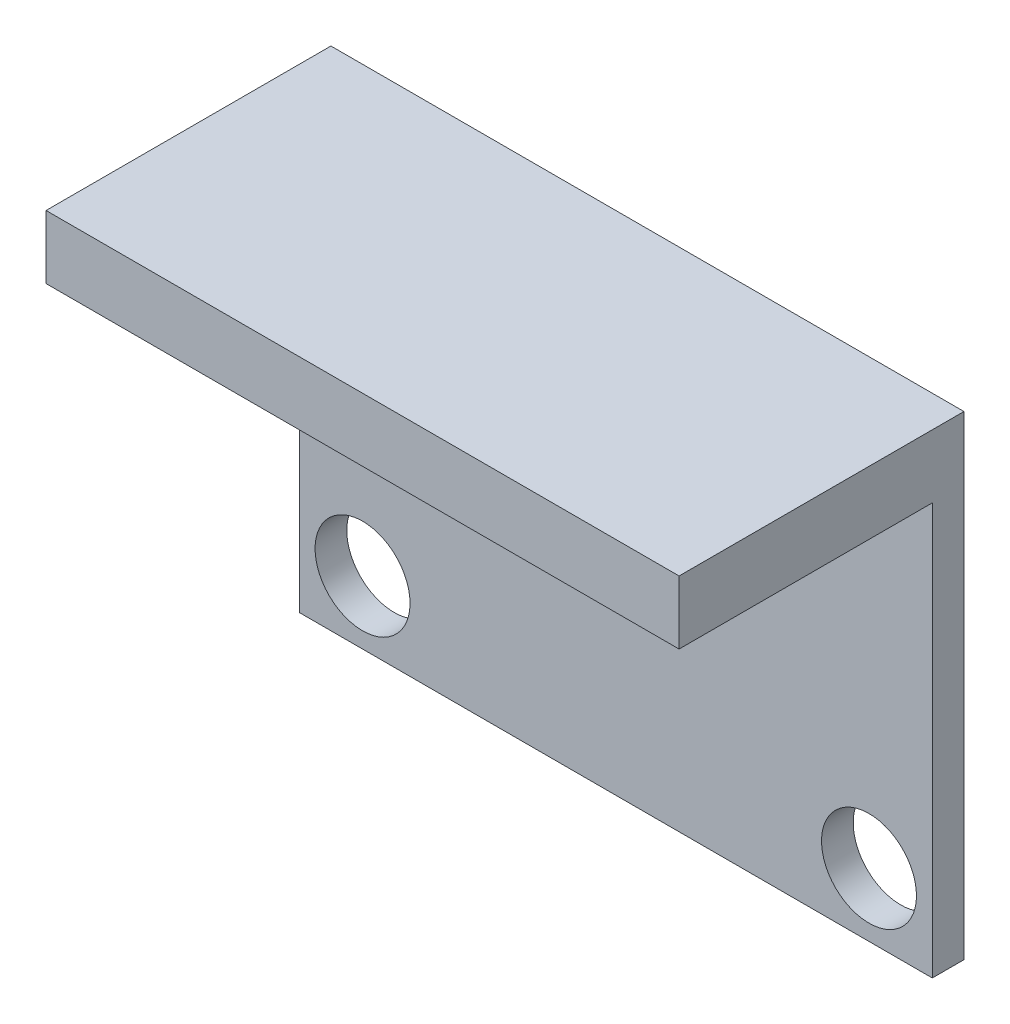
SolidWorks part; units mm, degrees
ref_plane "Plano frontal" through (0, 0, 0) normal (0, 0, 1) x (1, 0, 0)
ref_plane "Plano superior" through (0, 0, 0) normal (0, 1, 0) x (1, 0, 0)
ref_plane "Plano direito" through (0, 0, 0) normal (1, 0, 0) x (0, 0, -1)
sketch "Esboço1" plane through (0, 0, 0) normal (0, 0, 1) x (1, 0, 0)
  line L1 (-10, -7.5) -> (10, -7.5)
  line L2 (-10, -7.5) -> (-10, 7.5)
  line L3 (-10, 7.5) -> (10, 7.5)
  line L4 (10, -7.5) -> (10, 7.5)
  line L5 (-10, -7.5) -> (10, 7.5) construction
  line L6 (-10, 7.5) -> (10, -7.5) construction
  circle A0 centre (-8, -5.5) radius 1.5
  circle A1 centre (8, -5.5) radius 1.5
  point P0 (0, 0)
  dimension "D3" = 3
  dimension "D4" = 3
  dimension "D1" = 15
  dimension "D2" = 20
  dimension "D5" = 2
  dimension "D6" = 2
  dimension "D7" = 2
  dimension "D8" = 2
extrude "Ressalto-extrusão1" add sketch "Esboço1" along normal mid plane 1
sketch "Esboço2" plane through (0, 0, 0.5) normal (0, 0, 1) x (1, 0, 0)
  line L0 (0, 0) -> (0, 7.5) construction
  line L1 (10, 7.5) -> (-10, 7.5) construction
  line L2 (-10, 7.5) -> (-10, 5.5)
  line L3 (-10, 7.5) -> (-10, -7.5) construction
  line L4 (-10, 5.5) -> (10, 5.5)
  line L5 (10, -7.5) -> (10, 7.5) construction
  line L6 (10, 5.5) -> (10, 7.5)
  line L7 (10, 7.5) -> (-10, 7.5)
  dimension "D1" = 2
extrude "Ressalto-extrusão2" add sketch "Esboço2" along normal blind 8
sketch "Esboço3" plane through (0, 0, -0.5) normal (0, 0, -1) x (-1, 0, 0)
  line L10 (-10, 0) -> (10, 0) construction
  line L11 (10, 7.5) -> (10, -7.5) construction
  text T0 "FRENTE"
  point P5 (0, 0)
extrude "Corte-extrusão1" cut sketch "Esboço3" against normal blind 0.5
